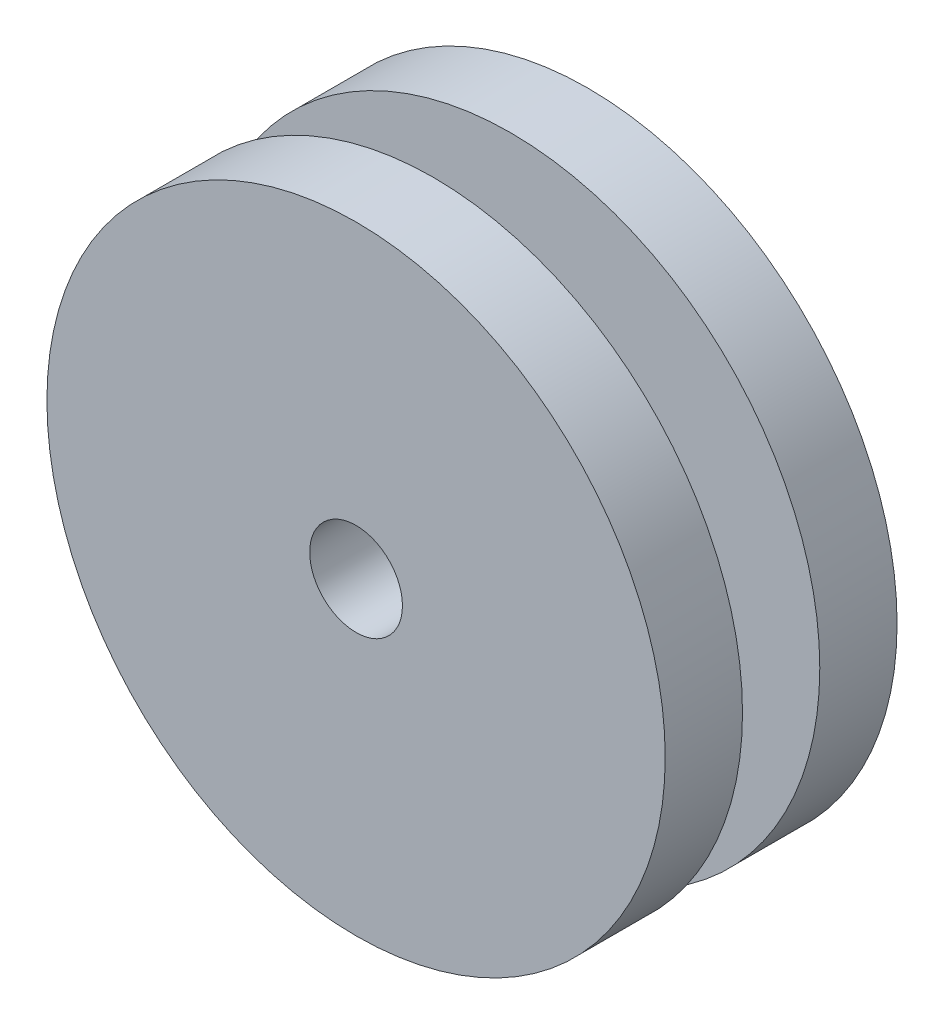
SolidWorks part; units mm, degrees
ref_plane "Front Plane" through (0, 0, 0) normal (0, 0, 1) x (1, 0, 0)
ref_plane "Top Plane" through (0, 0, 0) normal (0, 1, 0) x (1, 0, 0)
ref_plane "Right Plane" through (0, 0, 0) normal (1, 0, 0) x (0, 0, -1)
sketch "Sketch1" plane through (0, 0, 0) normal (0, 0, 1) x (1, 0, 0)
  circle A0 centre (0, 0) radius 20
extrude "Boss-Extrude1" add sketch "Sketch1" along normal blind 5
sketch "Sketch2" plane through (0, 0, 5) normal (0, 0, 1) x (1, 0, 0)
  circle A0 centre (0, 0) radius 10
extrude "Boss-Extrude2" add sketch "Sketch2" along normal blind 5
sketch "Sketch3" plane through (0, 0, 10) normal (0, 0, 1) x (1, 0, 0)
  circle A0 centre (0, 0) radius 20
extrude "Boss-Extrude3" add sketch "Sketch3" along normal blind 5
sketch "Sketch4" plane through (0, 0, 15) normal (0, 0, 1) x (1, 0, 0)
  circle A0 centre (0, 0) radius 3
extrude "Cut-Extrude1" cut sketch "Sketch4" against normal through all
